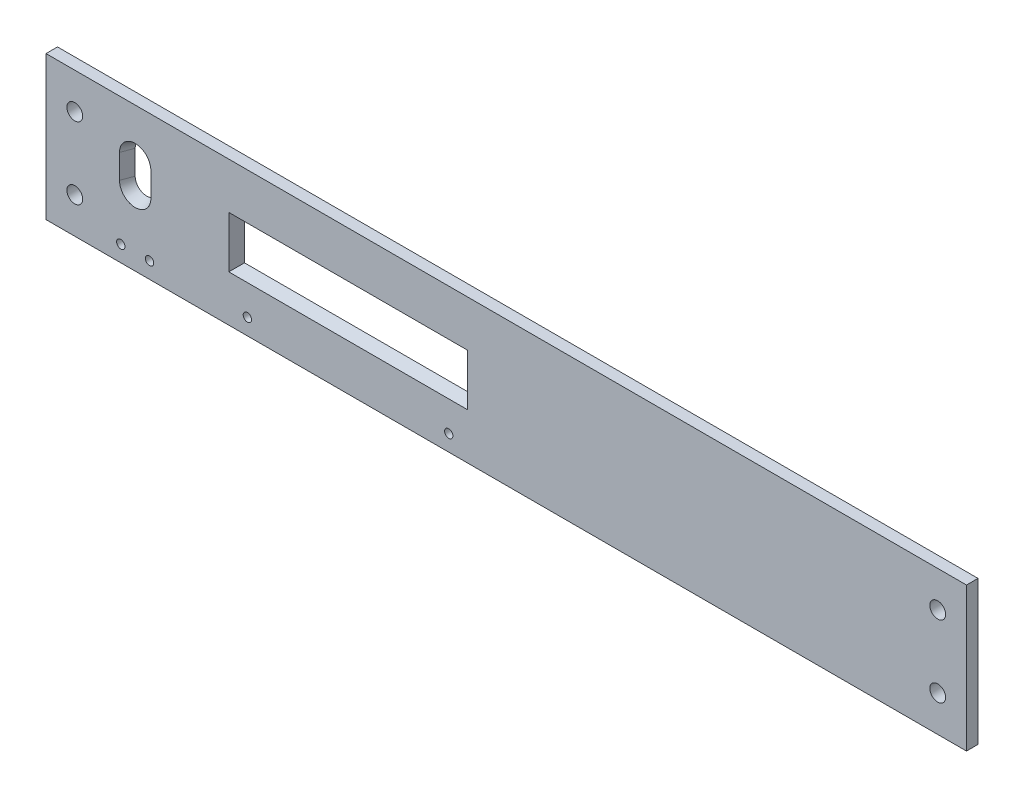
SolidWorks part; units mm, degrees
material "PLA"
ref_plane "Front Plane" through (0, 0, 0) normal (0, 0, 1) x (1, 0, 0)
ref_plane "Top Plane" through (0, 0, 0) normal (0, 1, 0) x (1, 0, 0)
ref_plane "Right Plane" through (0, 0, 0) normal (1, 0, 0) x (0, 0, -1)
sketch "Sketch1" plane through (0, 0, 0) normal (0, 0, 1) x (1, 0, 0)
  line L1 (0, 0) -> (320, 0)
  line L2 (0, 0) -> (0, 50)
  line L3 (0, 50) -> (320, 50)
  line L4 (320, 0) -> (320, 50)
  dimension "D1" = 320
  dimension "D2" = 50
extrude "Boss-Extrude1" add sketch "Sketch1" along normal blind 4
sketch "Sketch2" plane through (0, 0, 4) normal (0, 0, 1) x (1, 0, 0)
  line L0 (0, 37.5) -> (10, 37.5) construction
  line L1 (0, 50) -> (0, 0) construction
  line L2 (10, 37.5) -> (310, 37.5) construction
  line L3 (310, 37.5) -> (320, 37.5) construction
  line L4 (320, 0) -> (320, 50) construction
  line L5 (320, 50) -> (0, 50) construction
  point P11 (10, 37.5)
  point P12 (310, 37.5)
  dimension "D1" = 12.5
  dimension "D2" = 10
hole_wizard "M5 Clearance Hole1" positions "Sketch2" profile "Sketch4" hole size "M5" standard "ANSI Metric"
sketch "Sketch4" plane through (310, 37.5, 4) normal (1, 0, 0) x (0, -1, 0)
  line L0 (0, 0) -> (0, 15.6524)
  line L1 (0, 15.6524) -> (2.75, 14)
  line L2 (2.75, 14) -> (2.75, 0)
  line L5 (2.75, 0) -> (0, 0)
  line L10 (0, 15.6524) -> (-2.75, 14) construction
  line L11 (0, -6.35) -> (0, 107.95) construction
  dimension "Hole Dia." = 5.5
  dimension "Hole Depth" = 14
  dimension "Drill Angle" = 118
pattern_linear "LPattern1" count 2 spacing 25 along (0, -1, 0) of "M5 Clearance Hole1"
sketch "Sketch5" plane through (0, 0, 4) normal (0, 0, 1) x (1, 0, 0)
  line L1 (65, 32.5) -> (145, 32.5)
  line L2 (65, 32.5) -> (65, 17.5)
  line L3 (65, 17.5) -> (145, 17.5)
  line L4 (145, 32.5) -> (145, 17.5)
  line L5 (105, 32.5) -> (105, 17.5) construction
  line L6 (0, 50) -> (0, 0) construction
  line L7 (0, 25) -> (65, 25) construction
  dimension "D1" = 80
  dimension "D2" = 15
  dimension "D4" = 105
extrude "Cut-Extrude1" cut sketch "Sketch5" against normal through all
sketch "Sketch6" plane through (0, 0, 4) normal (0, 0, 1) x (1, 0, 0)
  line L0 (31, 24.6) -> (31, 33) construction
  line L1 (27, 24.6) -> (27, 33)
  line L2 (35, 24.6) -> (35, 33)
  line L3 (0, 50) -> (0, 0) construction
  line L4 (320, 50) -> (0, 50) construction
  arc A0 (27, 24.6) -> (35, 24.6) centre (31, 24.6) ccw
  arc A1 (35, 33) -> (27, 33) centre (31, 33) ccw
  point P2 (31, 28.8)
  dimension "D1" = 8
  dimension "D2" = 8.4
  dimension "D3" = 31
  dimension "D4" = 17
extrude "Cut-Extrude3" cut sketch "Sketch6" against normal through all
sketch "Sketch7" plane through (0, 0, 4) normal (0, 0, 1) x (1, 0, 0)
  line L0 (31, 20.6) -> (31, 5.6) construction
  line L1 (31, 5.6) -> (26, 5.6) construction
  line L2 (31, 5.6) -> (36, 5.6) construction
  line L3 (105, 17.5) -> (105, 5.6) construction
  line L4 (65, 17.5) -> (145, 17.5) construction
  line L5 (105, 5.6) -> (70, 5.6) construction
  line L7 (105, 5.6) -> (140, 5.6) construction
  arc A0 (27, 24.6) -> (35, 24.6) centre (31, 24.6) ccw construction
  point P6 (26, 5.6)
  point P7 (36, 5.6)
  point P23 (70, 5.6)
  point P26 (140, 5.6)
  point P27 (31, 28.655)
  point P28 (31, 20.6)
  dimension "D1" = 10
  dimension "D2" = 15
  dimension "D3" = 70
hole_wizard "M2.5 Clearance Hole1" positions "Sketch7" profile "Sketch8" hole size "M2.5" standard "ANSI Metric"
sketch "Sketch8" plane through (140, 5.6, 4) normal (1, 0, 0) x (0, -1, 0)
  line L0 (0, 0) -> (0, 14.8712)
  line L1 (0, 14.8712) -> (1.45, 14)
  line L2 (1.45, 14) -> (1.45, 0)
  line L5 (1.45, 0) -> (0, 0)
  line L10 (0, 14.8712) -> (-1.45, 14) construction
  line L11 (0, -6.35) -> (0, 107.95) construction
  dimension "Hole Dia." = 2.9
  dimension "Hole Depth" = 14
  dimension "Drill Angle" = 118
draft "Draft1" type of draft neutral plane draft angle 20 faces to draft 8 face at (145, 25, 2) face at (105, 32.5, 2) face at (65, 25, 2) face at (105, 17.5, 2) face at (35, 28.8, 2) face at (31, 35, 2) face at (27, 28.8, 2) face at (31, 22.6, 2) neutral plane through (0, 0, 0) neutral plane normal (0, 0, -1) reverse direction yes parameters "D1"=20
